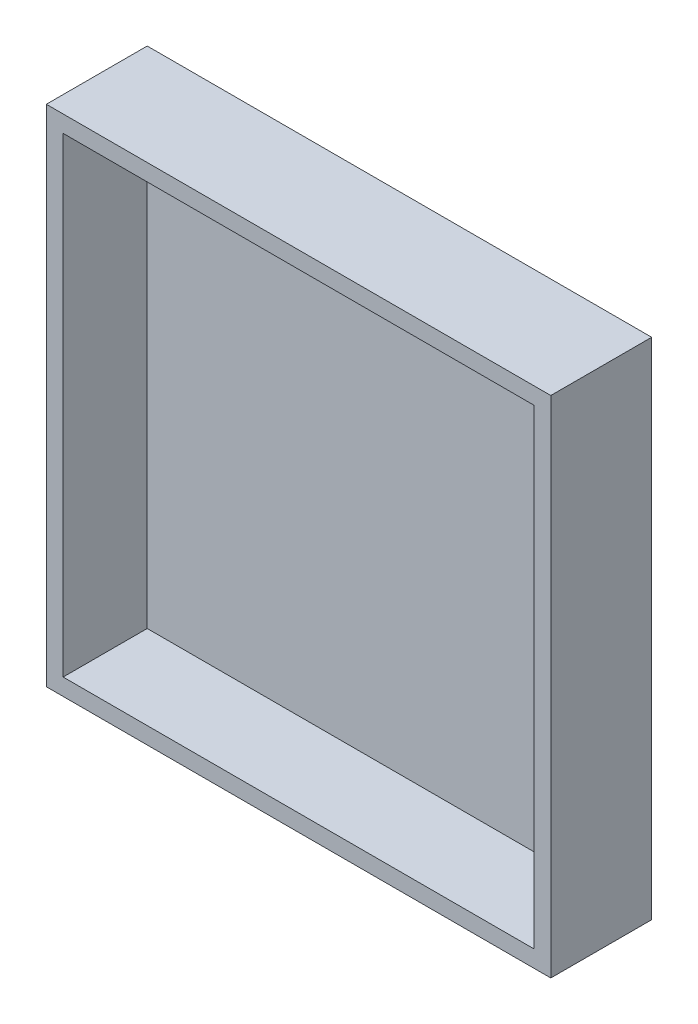
SolidWorks part; units mm, degrees
ref_plane "Front Plane" through (0, 0, 0) normal (0, 0, 1) x (1, 0, 0)
ref_plane "Top Plane" through (0, 0, 0) normal (0, 1, 0) x (1, 0, 0)
ref_plane "Right Plane" through (0, 0, 0) normal (1, 0, 0) x (0, 0, -1)
sketch "Sketch1" plane through (0, 0, 0) normal (0, 0, 1) x (1, 0, 0)
  line L1 (-150, 147.2419) -> (0, 147.2419)
  line L2 (-150, 147.2419) -> (-150, -2.7581)
  line L3 (-150, -2.7581) -> (0, -2.7581)
  line L4 (0, 147.2419) -> (0, -2.7581)
  line L5 (-150, 147.2419) -> (0, -2.7581) construction
  line L6 (-150, -2.7581) -> (0, 147.2419) construction
  point P0 (-75, 72.2419)
  dimension "D1" = 150
  dimension "D2" = 150
extrude "Boss-Extrude1" add sketch "Sketch1" along normal blind 30
shell "Shell1" thickness 5
